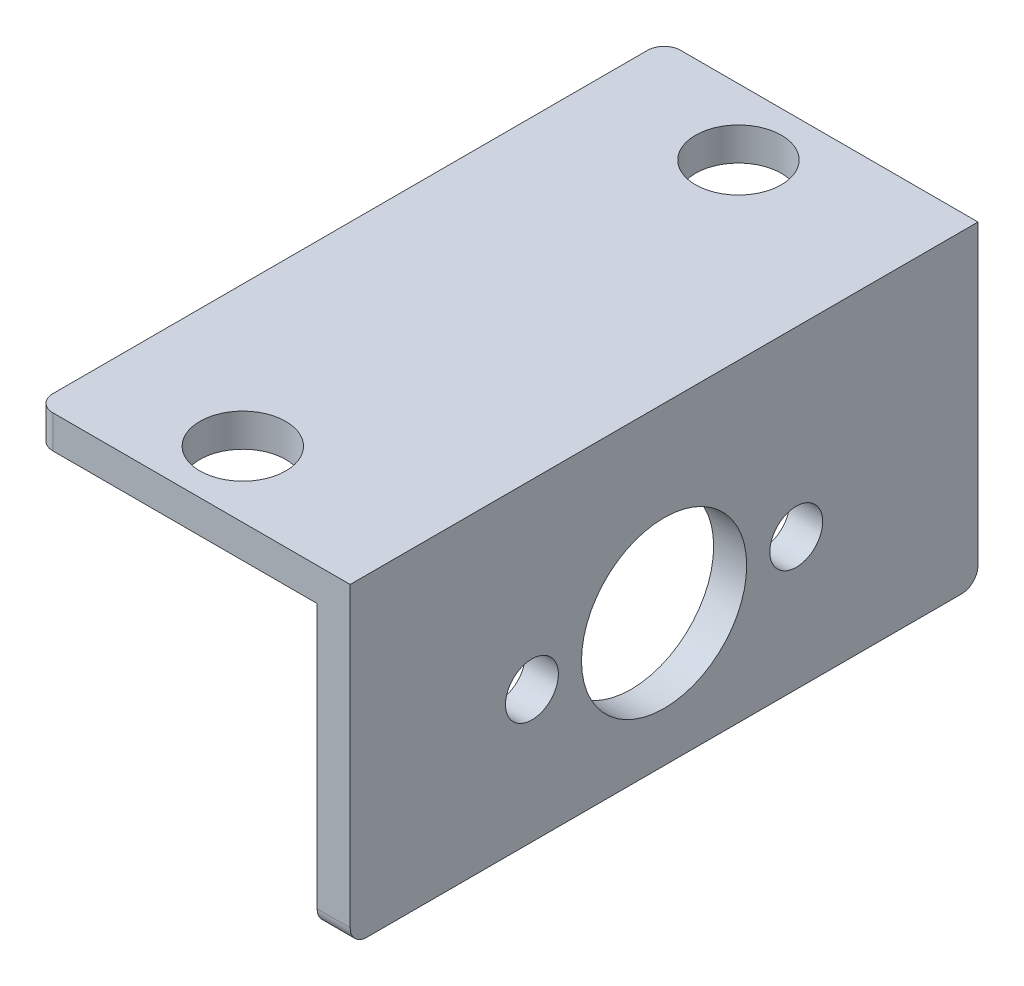
SolidWorks part; units mm, degrees
ref_plane "Front Plane" through (0, 0, 0) normal (0, 0, 1) x (1, 0, 0)
ref_plane "Top Plane" through (0, 0, 0) normal (0, 1, 0) x (1, 0, 0)
ref_plane "Right Plane" through (0, 0, 0) normal (1, 0, 0) x (0, 0, -1)
sketch "Sketch1" plane through (0, 0, 0) normal (0, 0, 1) x (1, 0, 0)
  line L0 (0, 0) -> (0, -19)
  line L1 (0, -19) -> (-2, -19)
  line L2 (-2, -19) -> (-2, -2)
  line L3 (-2, -2) -> (-19, -2)
  line L4 (-19, -2) -> (-19, 0)
  line L5 (-19, 0) -> (0, 0)
  dimension "D1" = 19
  dimension "D2" = 19
  dimension "D3" = 2
  dimension "D4" = 2
extrude "Boss-Extrude1" add sketch "Sketch1" along normal blind 38
sketch "Sketch2" plane through (0, 0, 0) normal (1, 0, 0) x (0, 0, -1)
  line L0 (-19, 0) -> (-19, -19) construction
  line L1 (-38, 0) -> (0, 0) construction
  line L2 (-38, -19) -> (0, -19) construction
  line L3 (-39.1264, -11) -> (0, -11) construction
  circle A0 centre (-19, -11) radius 5
  circle A1 centre (-27, -11) radius 1.6
  circle A2 centre (-11, -11) radius 1.6
  dimension "D2" = 10
  dimension "D3" = 3.2
  dimension "D4" = 16
  dimension "D1" = 11
extrude "Cut-Extrude1" cut sketch "Sketch2" against normal through all
sketch "Sketch3" plane through (0, -2, 0) normal (0, -1, 0) x (1, 0, 0)
  line L0 (-10.5, 38) -> (-10.5, 0) construction
  line L1 (-19, 38) -> (-2, 38) construction
  line L2 (-19, 0) -> (-2, 0) construction
  line L3 (-19, 19) -> (-2, 19) construction
  line L4 (-19, 38) -> (-19, 0) construction
  line L5 (-2, 38) -> (-2, 0) construction
  line L6 (0, 38) -> (0, 0) construction
  circle A0 centre (-10.5, 34) radius 2.6
  circle A1 centre (-10.5, 4) radius 2.6
  dimension "D1" = 5.2
  dimension "D2" = 30
extrude "Cut-Extrude2" cut sketch "Sketch3" against normal through all
fillet "Fillet1" radius 1 4 edges at (-19, -1, 38) (-19, -1, 0) (-1, -19, 0) (-1, -19, 38)
